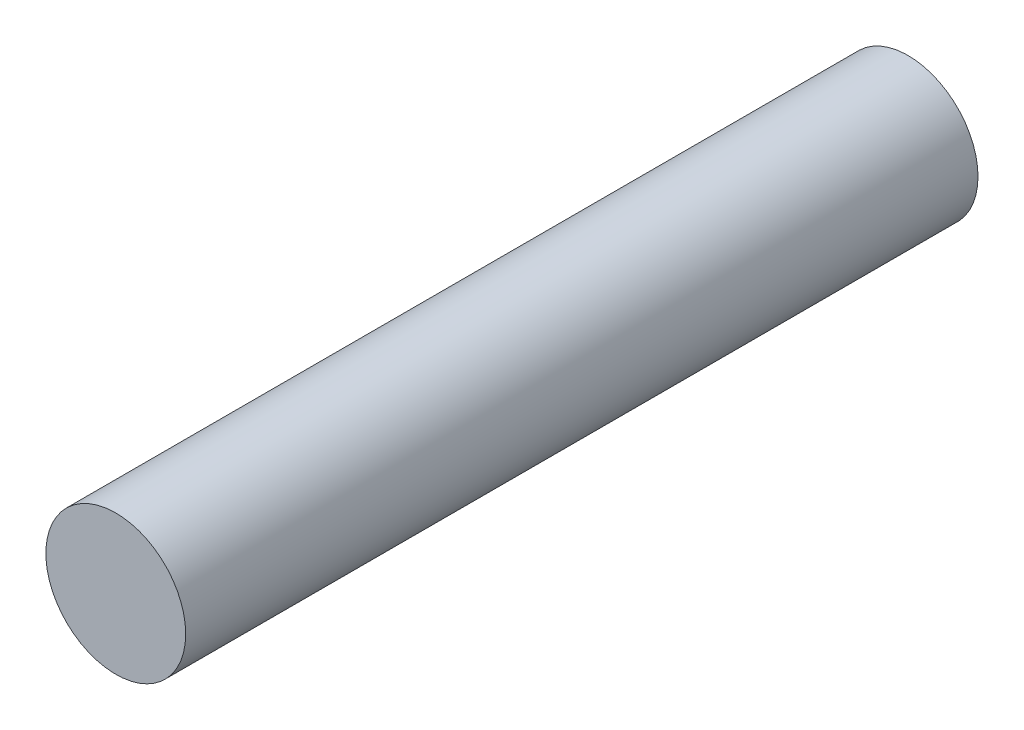
SolidWorks part; units mm, degrees
ref_plane "前视基准面" through (0, 0, 0) normal (0, 0, 1) x (1, 0, 0)
ref_plane "上视基准面" through (0, 0, 0) normal (0, 1, 0) x (1, 0, 0)
ref_plane "右视基准面" through (0, 0, 0) normal (1, 0, 0) x (0, 0, -1)
other "Configuration Table"
sketch "草图1" plane through (0, 0, 0) normal (0, 0, 1) x (1, 0, 0)
  circle A0 centre (0, 0) radius 1.5
  dimension "D1" = 3
extrude "凸台-拉伸1" add sketch "草图1" along normal blind 17
sketch "草图3" plane through (0, 0, 0) normal (0, 1, 0) x (1, 0, 0)
  line L0 (1.5, 0) -> (1.5, -17) construction
